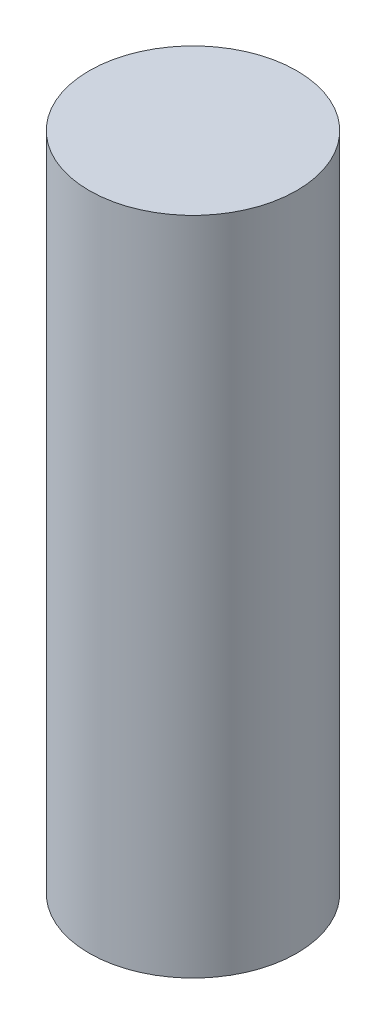
SolidWorks part; units mm, degrees
material "PBT General Purpose"
ref_plane "Front Plane" through (0, 0, 0) normal (0, 0, 1) x (1, 0, 0)
ref_plane "Top Plane" through (0, 0, 0) normal (0, 1, 0) x (1, 0, 0)
ref_plane "Right Plane" through (0, 0, 0) normal (1, 0, 0) x (0, 0, -1)
sketch "Sketch1" plane through (0, 0, 0) normal (0, 1, 0) x (1, 0, 0)
  circle A0 centre (0, 0) radius 27.5
extrude "Boss-Extrude1" add sketch "Sketch1" along normal blind 175
